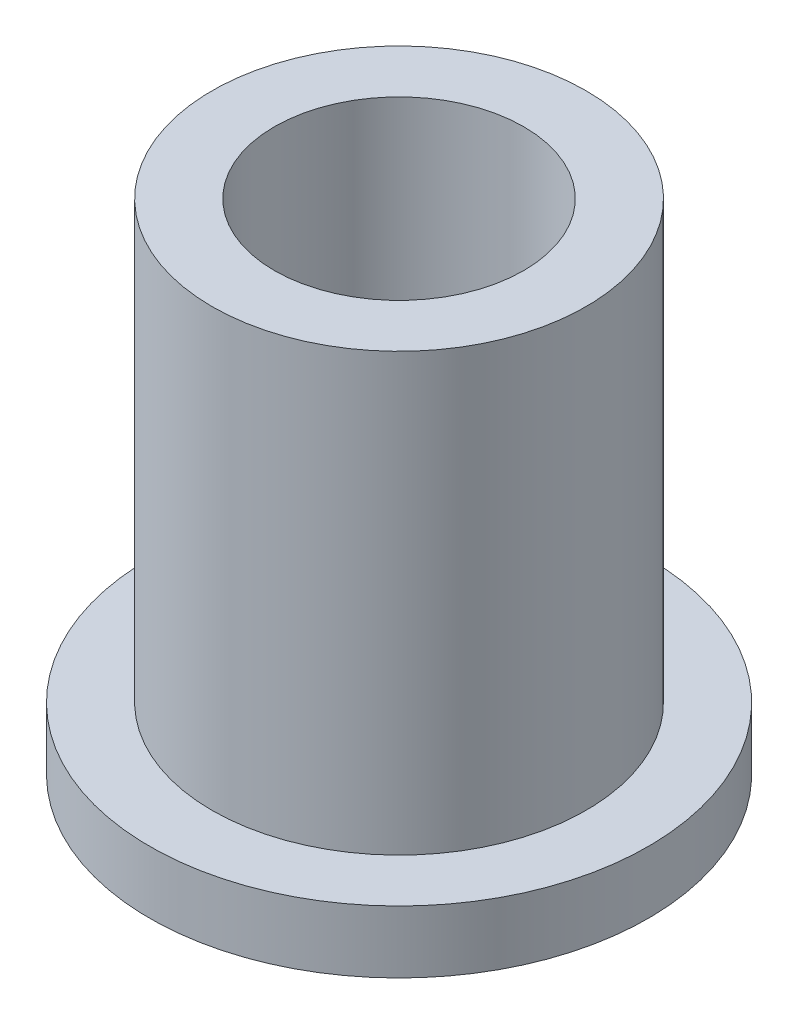
SolidWorks part; units mm, degrees
material "Commercial Bronze, UNS C22000 (90-10 Bronze)"
ref_plane "Front Plane" through (0, 0, 0) normal (0, 0, 1) x (1, 0, 0)
ref_plane "Top Plane" through (0, 0, 0) normal (0, 1, 0) x (1, 0, 0)
ref_plane "Right Plane" through (0, 0, 0) normal (1, 0, 0) x (0, 0, -1)
sketch "Sketch1" plane through (0, 0, 0) normal (0, 1, 0) x (1, 0, 0)
  circle A0 centre (0, 0) radius 3.175
  circle A1 centre (0, 0) radius 4.7625
  dimension "D1" = 6.35
  dimension "D2" = 9.525
extrude "Boss-Extrude1" add sketch "Sketch1" along normal blind 12.7
sketch "Sketch2" plane through (0, 0, 0) normal (0, -1, 0) x (1, 0, 0)
  circle A0 centre (0, 0) radius 4.7625 construction
  circle A1 centre (0, 0) radius 4.7625
  circle A2 centre (0, 0) radius 6.35
  dimension "D1" = 12.7
extrude "Boss-Extrude2" add sketch "Sketch2" against normal blind 1.5875
